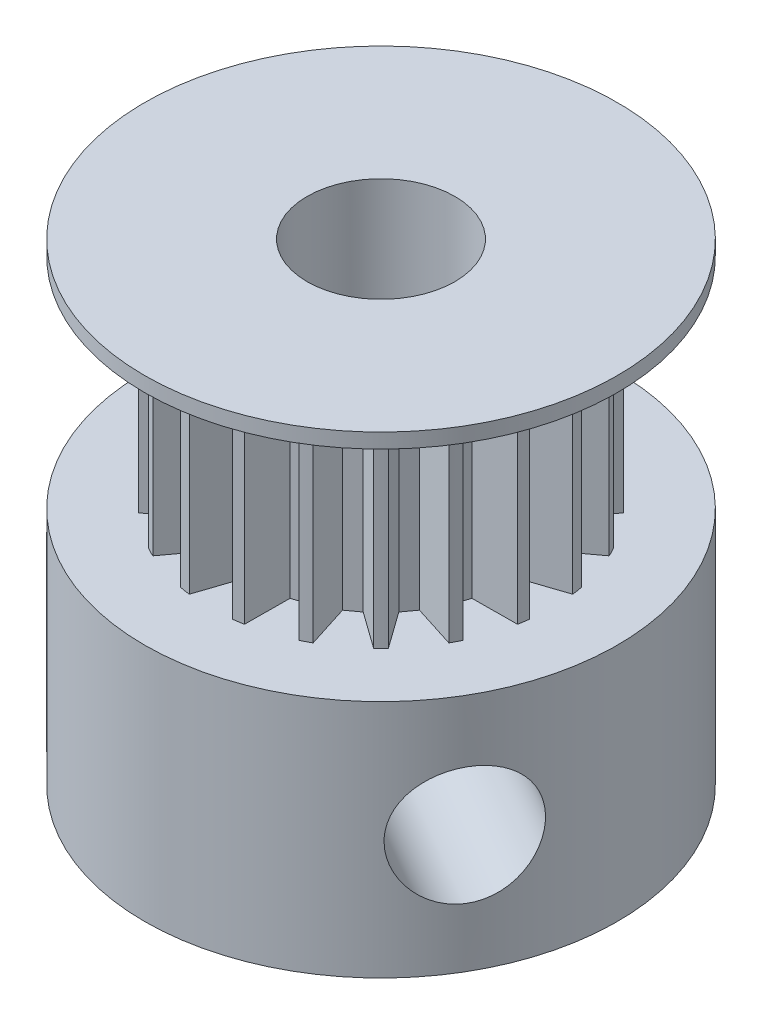
SolidWorks part; units mm, degrees
ref_plane "Front Plane" through (0, 0, 0) normal (0, 0, 1) x (1, 0, 0)
ref_plane "Top Plane" through (0, 0, 0) normal (0, 1, 0) x (1, 0, 0)
ref_plane "Right Plane" through (0, 0, 0) normal (1, 0, 0) x (0, 0, -1)
sketch "Sketch11" plane through (0, 0, 0) normal (0, 1, 0) x (1, 0, 0)
  circle A0 centre (0, 0) radius 8
  dimension "D1" = 16
extrude "Boss-Extrude5" add sketch "Sketch11" along normal blind 15.5 contours A0
sketch "Sketch12" plane through (0, 15.5, 0) normal (0, 1, 0) x (1, 0, 0)
  circle A0 centre (0, 0) radius 5.9
  circle A1 centre (0, 0) radius 8 construction
  circle A2 centre (0, 0) radius 8
  circle A3 centre (0, 0) radius 2.5
  dimension "D1" = 2.1
  dimension "D2" = 5
extrude "Cut-Extrude9" cut sketch "Sketch12" against normal through all contours A3
sketch "Sketch14" plane through (0, 15.5, 0) normal (0, 1, 0) x (1, 0, 0)
  circle A0 centre (0, 0) radius 5.8
  circle A1 centre (0, 0) radius 8 construction
  circle A2 centre (0, 0) radius 8
  point P3 (0, 0)
  dimension "D1" = 2.2
extrude "Cut-Extrude11" cut sketch "Sketch14" against normal blind 7.4 contours A2 | A0
sketch "Sketch15" plane through (0, 15.5, 0) normal (0, 1, 0) x (1, 0, 0)
  line L0 (0, 0) -> (0, 5.8) construction
  line L9 (-0.75, 5.8) -> (0.75, 5.8)
  line L10 (-0.75, 5.8) -> (-0.25, 4.3)
  line L11 (-0.25, 4.3) -> (0.25, 4.3)
  line L12 (0.25, 4.3) -> (0.75, 5.8)
  circle A0 centre (0, 0) radius 5.8 construction
  point P8 (0, 4.3)
  dimension "D1" = 1.5
  dimension "D2" = 0.5
  dimension "D3" = 1.5
extrude "Cut-Extrude12" cut sketch "Sketch15" against normal blind 7.4 contours L12 L9 L10 L11
pattern_circular "CirPattern5" count 20 over 360 about axis through (0, 0, 0) along (0, 1, 0) of "Cut-Extrude12"
sketch "Sketch16" plane through (0, 15.5, 0) normal (0, 1, 0) x (1, 0, 0)
  circle A0 centre (0, 0) radius 8
extrude "Boss-Extrude6" add sketch "Sketch16" along normal blind 0.5 contours A0
sketch "Sketch17" plane through (0, 15.5, 0) normal (0, -1, 0) x (1, 0, 0)
  circle A0 centre (0, 0) radius 2.5
extrude "Cut-Extrude13" cut sketch "Sketch17" against normal through all contours A0
sketch "Sketch18" plane through (0, 0, 0) normal (0, 0, 1) x (1, 0, 0)
  circle A1 centre (0, 4) radius 2
  dimension "D1" = 4
  dimension "D2" = 4
extrude "Cut-Extrude14" cut sketch "Sketch18" against normal up to next
pattern_circular "CirPattern6" count 3 over 360 about axis through (0, 0, 0) along (0, 1, 0) of "Cut-Extrude14"
